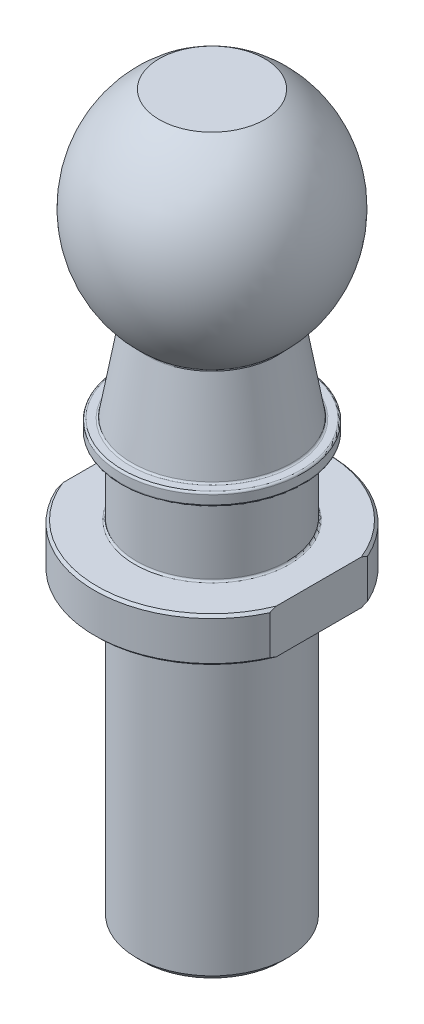
SolidWorks part; units mm, degrees
ref_plane "Plano frontal" through (0, 0, 0) normal (0, 0, 1) x (1, 0, 0)
ref_plane "Plano superior" through (0, 0, 0) normal (0, 1, 0) x (1, 0, 0)
ref_plane "Plano direito" through (0, 0, 0) normal (1, 0, 0) x (0, 0, -1)
sketch "Esboço1" plane through (0, 0, 0) normal (0, 0, 1) x (1, 0, 0)
  line L0 (0, 52.4807) -> (0, -52.9589) construction
  line L1 (0, -52.9589) -> (6, -52.9589)
  line L2 (6, -52.9589) -> (6, -28.7589)
  line L3 (6, -28.7589) -> (9.35, -28.7589)
  line L4 (9.35, -28.7589) -> (9.35, -25.2589)
  line L5 (9.35, -25.2589) -> (6, -25.2589)
  line L6 (6, -25.2589) -> (6, -19.2589)
  line L7 (6, -19.2589) -> (7.25, -19.2589)
  line L8 (7.25, -19.2589) -> (7.25, -18.2589)
  line L9 (7.25, -18.2589) -> (6.4, -18.2589)
  line L10 (6.4, -18.2589) -> (5.175, -11.2589)
  line L11 (4.2023, 4.4411) -> (0, 4.4411)
  line L12 (0, 4.4411) -> (0, -52.9589)
  arc A0 (5.175, -11.2589) -> (4.2023, 4.4411) centre (-0.9606, -3.7589) ccw
  dimension "D7" = 9.69
  dimension "D1" = 6
  dimension "D2" = 9.35
  dimension "D3" = 6
  dimension "D4" = 7.25
  dimension "D5" = 6.4
  dimension "D6" = 5.175
  dimension "D8" = 24.2
  dimension "D9" = 3.5
  dimension "D10" = 6
  dimension "D11" = 1
  dimension "D12" = 7
  dimension "D13" = 25
  dimension "D14" = 57.4
revolve "Revolução1" add sketch "Esboço1" angle 360 about L0
fillet "Filete3" radius 0.15 5 edges at (0, -18.2589, 7.25) (0, -19.2589, 7.25) (0, -19.2589, 6) (0, -18.2589, 6.4) (0, -11.2589, 5.175)
chamfer "Chanfro1" distance 0.2 angle 45 2 edges at (0, -28.7589, 9.35) (0, -25.2589, 9.35)
fillet "Filete4" radius 0.15 1 edges at (0, -25.2589, 6)
chamfer "Chanfro2" distance 0.5 angle 45 1 edges at (0, -52.9589, 6)
sketch "Esboço2" plane through (0, -25.2589, 0) normal (0, 1, 0) x (1, 0, 0)
  line L0 (11.6973, -13.7348) -> (8.5, -13.7348)
  line L1 (-8.5, -13.7348) -> (-8.5, 10.9528)
  line L2 (-8.5, 10.9528) -> (-11.6973, 10.9528)
  line L3 (-11.6973, 10.9528) -> (-11.6973, -13.7348)
  line L4 (-11.6973, -13.7348) -> (-8.5, -13.7348)
  line L5 (0, 0) -> (0, -16.0721) construction
  line L6 (11.6973, 10.9528) -> (11.6973, -13.7348)
  line L7 (8.5, 10.9528) -> (11.6973, 10.9528)
  line L8 (8.5, -13.7348) -> (8.5, 10.9528)
extrude "Corte-extrusão1" cut sketch "Esboço2" against normal through all
sketch "Esboço3" plane through (0, -52.9589, 0) normal (0, -1, 0) x (1, 0, 0)
  line L1 (0.5777, 2.8284) -> (-2.1606, 1.9145)
  line L2 (-2.1606, 1.9145) -> (-2.7383, -0.9139)
  line L3 (-2.7383, -0.9139) -> (-0.5777, -2.8284)
  line L4 (-0.5777, -2.8284) -> (2.1606, -1.9145)
  line L5 (2.1606, -1.9145) -> (2.7383, 0.9139)
  line L6 (2.7383, 0.9139) -> (0.5777, 2.8284)
  circle A0 centre (0, 0) radius 2.5 construction
  dimension "D1" = 5
extrude "Corte-extrusão2" cut sketch "Esboço3" against normal blind 5
